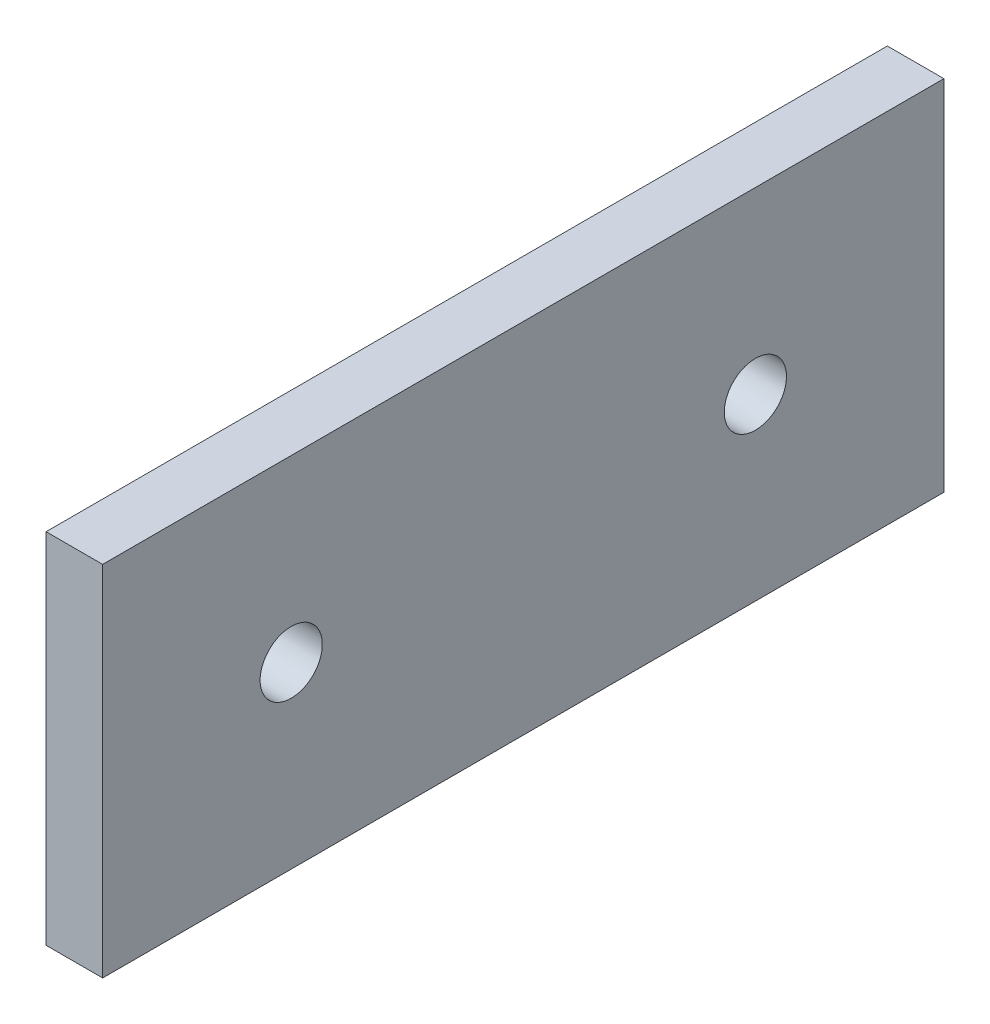
SolidWorks part; units mm, degrees
ref_plane "前视基准面" through (0, 0, 0) normal (0, 0, 1) x (1, 0, 0)
ref_plane "上视基准面" through (0, 0, 0) normal (0, 1, 0) x (1, 0, 0)
ref_plane "右视基准面" through (0, 0, 0) normal (1, 0, 0) x (0, 0, -1)
sketch "草图1" plane through (0, 0, 0) normal (0, 0, 1) x (1, 0, 0)
  line L1 (0, 0) -> (13, 0)
  line L2 (0, 0) -> (0, 13)
  line L3 (0, 13) -> (13, 13)
  line L4 (13, 0) -> (13, 13)
  dimension "D1" = 13
  dimension "D2" = 13
extrude "拉伸-薄壁1" add sketch "草图1" along normal blind 44.62 thin
sketch "草图2" plane through (-3, 0, 0) normal (-1, 0, 0) x (0, 0, 1)
  line L0 (0, 16) -> (0, -3) construction
  line L1 (44.62, 16) -> (44.62, -3) construction
  circle A0 centre (10, 6.5) radius 1.65
  circle A1 centre (34.62, 6.5) radius 1.65
  dimension "D1" = 3.3
  dimension "D2" = 3.3
  dimension "D3" = 10
  dimension "D4" = 10
extrude "切除-拉伸1" cut sketch "草图2" against normal blind 30
sketch "草图3" plane through (16, 0, 0) normal (1, 0, 0) x (0, 0, -1)
  line L1 (-44.62, 16) -> (0, 16)
  line L2 (-44.62, 16) -> (-44.62, -3)
  line L3 (-44.62, -3) -> (0, -3)
  line L4 (0, 16) -> (0, -3)
extrude "切除-拉伸2" cut sketch "草图3" against normal blind 16
sketch "草图4" plane through (0, 0, 0) normal (1, 0, 0) x (0, 0, -1)
  line L0 (0, 16) -> (0, -3) construction
  line L1 (-23.62, 12.85) -> (-21, 12.85)
  line L2 (-23.62, 12.85) -> (-23.62, 0.15)
  line L3 (-23.62, 0.15) -> (-21, 0.15)
  line L4 (-21, 12.85) -> (-21, 0.15)
  line L5 (-44.62, 16) -> (-44.62, -3) construction
  line L6 (-44.62, -3) -> (0, -3) construction
  line L7 (0, 16) -> (-44.62, 16) construction
  point P8 (-21, 6.5)
  dimension "D1" = 21
  dimension "D2" = 21
  dimension "D3" = 12.7
  dimension "D4" = 9.5
  dimension "D5" = 3.15
  dimension "D6" = 3.15
extrude "凸台-拉伸1" [suppressed] add sketch "草图4" along normal blind 2.9
chamfer "倒角1" [suppressed] distance 2.5 angle 45
